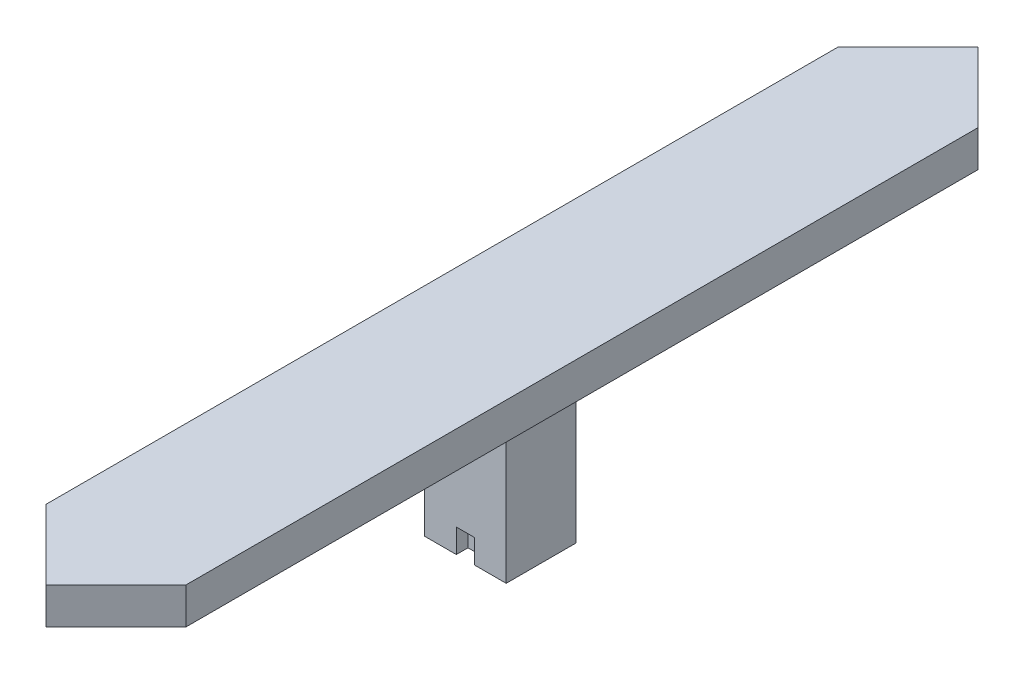
SolidWorks part; units mm, degrees
ref_plane "Front Plane" through (0, 0, 0) normal (0, 0, 1) x (1, 0, 0)
ref_plane "Top Plane" through (0, 0, 0) normal (0, 1, 0) x (1, 0, 0)
ref_plane "Right Plane" through (0, 0, 0) normal (1, 0, 0) x (0, 0, -1)
sketch "Sketch1" plane through (0, 0, 0) normal (0, 1, 0) x (1, 0, 0)
  line L0 (0, 5) -> (0, -13) construction
  line L1 (0, 0) -> (6, -6)
  line L2 (6, -6) -> (6, -74)
  line L3 (6, -74) -> (0, -80)
  line L4 (-6, -74) -> (0, -80)
  line L5 (-6, -6) -> (-6, -74)
  line L6 (0, 0) -> (-6, -6)
  dimension "D1" = 135
  dimension "D2" = 135
  dimension "D4" = 68
  dimension "D3" = 12
  dimension "D5" = 0
  dimension "D6" = 80
extrude "Boss-Extrude1" add sketch "Sketch1" along normal blind 3.125
sketch "Sketch2" plane through (0, 0, 0) normal (0, -1, 0) x (1, 0, 0)
  line L0 (0, 0) -> (0, 80) construction
  line L1 (3.5, 38) -> (-3.5, 38)
  line L2 (3.5, 38) -> (3.5, 42)
  line L3 (3.5, 42) -> (-3.5, 42)
  line L4 (-3.5, 38) -> (-3.5, 42)
  line L5 (3.5, 38) -> (-3.5, 42) construction
  line L6 (3.5, 42) -> (-3.5, 38) construction
  line L7 (6, 40) -> (-6, 40) construction
  line L8 (6, 74) -> (6, 6) construction
  line L9 (-6, 6) -> (-6, 74) construction
  point P0 (0, 40)
  dimension "D1" = 7
  dimension "D2" = 0
  dimension "D3" = 4
  dimension "D4" = 0
extrude "Boss-Extrude2" add sketch "Sketch2" along normal blind 13
sketch "Sketch3" plane through (0, 0, 42) normal (0, 0, 1) x (1, 0, 0)
  line L0 (0, -13) -> (0, 0) construction
  line L1 (3.5, -13) -> (-3.5, -13) construction
  line L2 (3.5, 0) -> (-3.5, 0) construction
  line L3 (3.5, -14.64) -> (-3.5, -14.64)
  line L8 (3.5, -13) -> (3.5, 0) construction
  line L9 (-3.5, -13) -> (-3.5, 0) construction
  line L10 (2.25, -2.8) -> (3.5, -14.64)
  line L11 (-2.25, -2.8) -> (-3.5, -14.64)
  arc A0 (2.25, -2.8) -> (-2.25, -2.8) centre (0, -2.8) ccw
  point P6 (0, -6.5)
  dimension "D1" = 4.5
  dimension "D2" = 11.84
  dimension "D3" = 2.8
extrude "Cut-Extrude1" cut sketch "Sketch3" against normal blind 2.5
sketch "Sketch4" plane through (0, 0, 42) normal (0, 0, 1) x (1, 0, 0)
  line L1 (3.5, 0) -> (-3.5, 0)
  line L2 (3.5, 0) -> (3.5, -13)
  line L3 (3.5, -13) -> (-3.5, -13)
  line L4 (-3.5, 0) -> (-3.5, -13)
extrude "Boss-Extrude3" add sketch "Sketch4" along normal blind 2
sketch "Sketch5" plane through (0, 0, 44) normal (0, 0, 1) x (1, 0, 0)
  line L0 (-3.5, -13) -> (3.5, -13) construction
  line L1 (0.7786, -15.0496) -> (-0.7786, -15.0496)
  line L2 (0.7786, -15.0496) -> (0.7786, -10.9504)
  line L3 (0.7786, -10.9504) -> (-0.7786, -10.9504)
  line L4 (-0.7786, -15.0496) -> (-0.7786, -10.9504)
  line L5 (0.7786, -15.0496) -> (-0.7786, -10.9504) construction
  line L6 (0.7786, -10.9504) -> (-0.7786, -15.0496) construction
  point P0 (0, -13)
extrude "Cut-Extrude2" cut sketch "Sketch5" against normal blind 1
equation "\"D2@Sketch1\"=\"D1@Sketch1\""
